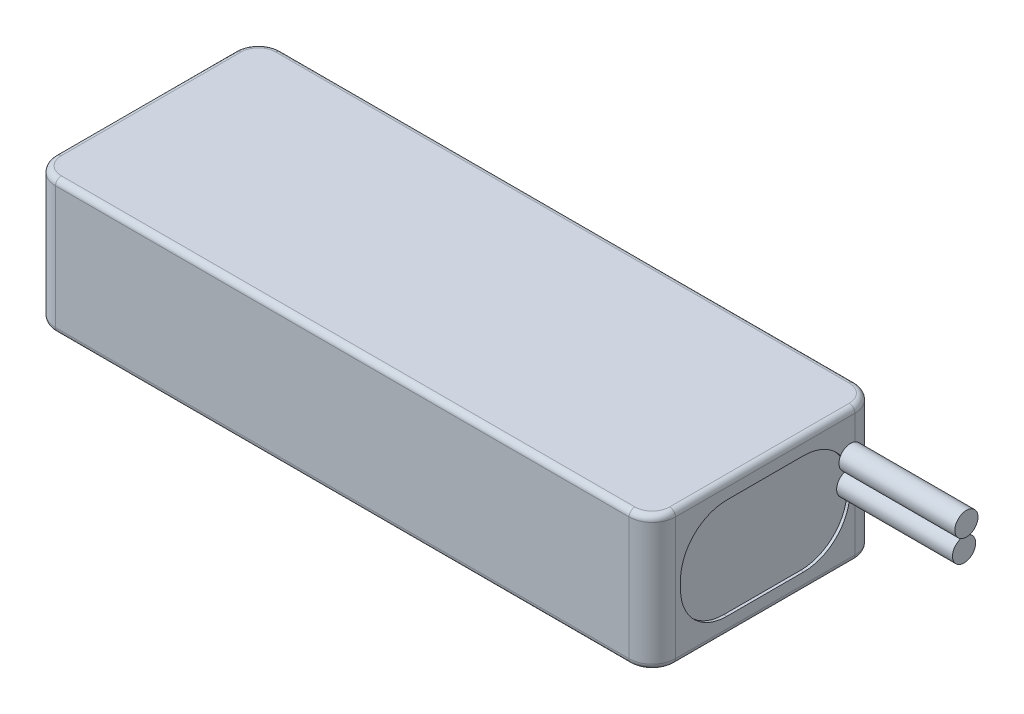
SolidWorks part; units mm, degrees
ref_plane "Front Plane" through (0, 0, 0) normal (0, 0, 1) x (1, 0, 0)
ref_plane "Top Plane" through (0, 0, 0) normal (0, 1, 0) x (1, 0, 0)
ref_plane "Right Plane" through (0, 0, 0) normal (1, 0, 0) x (0, 0, -1)
ref_plane "Plane1" through (0, 0, -15) normal (0, 0, -1) x (-1, 0, 0)
sketch "Sketch1" plane through (0, 0, -15) normal (0, 0, -1) x (-1, 0, 0)
  line L0 (-69, -22) -> (38, -22)
  line L1 (38, -22) -> (38, 1.18)
  line L2 (38, 1.18) -> (-69, 1.18)
  line L3 (-69, 1.18) -> (-69, -22)
  line L4 (-69, -10.41) -> (38, -10.41) construction
  line L5 (-15.5, 1.18) -> (-15.5, -22) construction
  dimension "D1" = 23.18
  dimension "D2" = 107
extrude "Boss-Extrude1" add sketch "Sketch1" against normal blind 39
sketch "Sketch2" plane through (69, 0, 0) normal (1, 0, 0) x (0, 0, -1)
  line L0 (-19.125, -9.7175) -> (-19.125, -11.1025)
  line L1 (-11.125, -19.1025) -> (2.125, -19.1025)
  line L2 (10.125, -11.1025) -> (10.125, -9.7175)
  line L3 (2.125, -1.7175) -> (-11.125, -1.7175)
  line L4 (-24, 1.18) -> (15, -22) construction
  line L5 (15, 1.18) -> (-24, -22) construction
  line L6 (-19.125, -1.7175) -> (10.125, -19.1025) construction
  line L7 (10.125, -1.7175) -> (-19.125, -19.1025) construction
  line L12 (-24, 1.18) -> (15, 1.18) construction
  line L13 (-24, 1.18) -> (-24, -22) construction
  line L14 (-24, -22) -> (15, -22) construction
  line L15 (15, 1.18) -> (15, -22) construction
  line L16 (-24, 1.18) -> (15, -22) construction
  line L17 (-24, -22) -> (15, 1.18) construction
  arc A0 (-19.125, -11.1025) -> (-11.125, -19.1025) centre (-11.125, -11.1025) ccw
  arc A1 (2.125, -19.1025) -> (10.125, -11.1025) centre (2.125, -11.1025) ccw
  arc A2 (10.125, -9.7175) -> (2.125, -1.7175) centre (2.125, -9.7175) ccw
  arc A3 (-19.125, -9.7175) -> (-11.125, -1.7175) centre (-11.125, -9.7175) cw
  point P16 (-4.5, -10.41)
  dimension "D3" = 8
  dimension "D1" = 29.25
  dimension "D2" = 39
extrude "Cut-Extrude1" cut sketch "Sketch2" against normal blind 0.5
sketch "Sketch3" plane through (-38, 0, 0) normal (-1, 0, 0) x (0, 0, 1)
  line L0 (11.125, -1.7175) -> (-2.125, -1.7175)
  line L1 (-10.125, -9.7175) -> (-10.125, -11.1025)
  line L2 (-2.125, -19.1025) -> (11.125, -19.1025)
  line L3 (19.125, -11.1025) -> (19.125, -9.7175)
  line L4 (-10.125, -1.7175) -> (19.125, -19.1025) construction
  line L5 (19.125, -1.7175) -> (-10.125, -19.1025) construction
  line L6 (-15, 1.18) -> (24, -22) construction
  line L7 (24, -22) -> (-15, -22) construction
  line L8 (-15, -22) -> (24, 1.18) construction
  arc A0 (-10.125, -11.1025) -> (-2.125, -19.1025) centre (-2.125, -11.1025) ccw
  arc A1 (11.125, -19.1025) -> (19.125, -11.1025) centre (11.125, -11.1025) ccw
  arc A2 (11.125, -1.7175) -> (19.125, -9.7175) centre (11.125, -9.7175) cw
  arc A3 (-2.125, -1.7175) -> (-10.125, -9.7175) centre (-2.125, -9.7175) ccw
  dimension "D3" = 8
  dimension "D1" = 29.25
  dimension "D2" = 39
extrude "Cut-Extrude2" cut sketch "Sketch3" against normal blind 0.5
fillet "Fillet1" radius 4 4 edges at (-38, -10.41, -15) (-38, -10.41, 24) (69, -10.41, -15) (69, -10.41, 24)
fillet "Fillet2" radius 1 16 edges at (67.8284, 1.18, -13.8284) (69, 1.18, 4.5) (15.5, 1.18, -15) (67.8284, 1.18, 22.8284) (-36.8284, 1.18, -13.8284) (15.5, 1.18, 24) (-38, 1.18, 4.5) (-36.8284, 1.18, 22.8284) (-38, -22, 4.5) (-36.8284, -22, -13.8284) (-36.8284, -22, 22.8284) (15.5, -22, -15) (15.5, -22, 24) (67.8284, -22, -13.8284) (67.8284, -22, 22.8284) (69, -22, 4.5)
sketch "Sketch4" plane through (0, 0, 24) normal (0, 0, 1) x (1, 0, 0)
  line L0 (-34, -10.41) -> (65, -10.41) construction
  line L1 (-34, 0.18) -> (-34, -21) construction
  line L2 (65, -21) -> (65, 0.18) construction
  line L3 (15.5, 25.9735) -> (15.5, -21) construction
  line L4 (-34, -21) -> (65, -21) construction
  circle A0 centre (15.5, -10.41) radius 0.5026
sketch "Sketch5" plane through (69, 0, 0) normal (1, 0, 0) x (0, 0, -1)
  circle A0 centre (10.228, -5.938) radius 2
  dimension "D1" = 4
extrude "Boss-Extrude2" add sketch "Sketch5" along normal blind 20 contours A0
sketch "Sketch7" plane through (68.5, 0, 0) normal (1, 0, 0) x (0, 0, -1)
  circle A0 centre (10.3254, -10.1133) radius 2
  dimension "D1" = 4
extrude "Boss-Extrude3" add sketch "Sketch7" along normal blind 20
equation "\"D1@Sketch3\"=\"D2@Sketch3\" * .75"
equation "\"D1@Sketch2\"=\"D2@Sketch2\"* .75"
